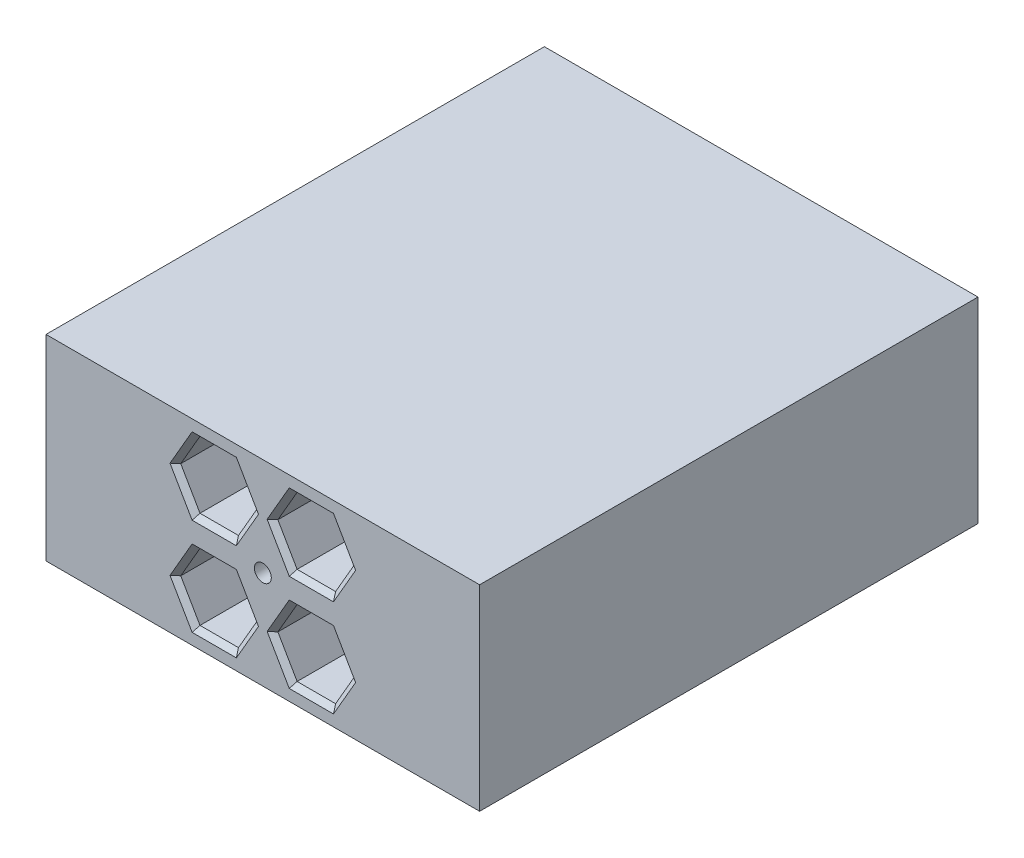
SolidWorks part; units mm, degrees
ref_plane "Front Plane" through (0, 0, 0) normal (0, 0, 1) x (1, 0, 0)
ref_plane "Top Plane" through (0, 0, 0) normal (0, 1, 0) x (1, 0, 0)
ref_plane "Right Plane" through (0, 0, 0) normal (1, 0, 0) x (0, 0, -1)
sketch "Sketch1" plane through (0, 0, 0) normal (0, 0, 1) x (1, 0, 0)
  line L1 (0, 0) -> (44.2, 0)
  line L2 (0, 0) -> (0, 20)
  line L3 (0, 20) -> (44.2, 20)
  line L4 (44.2, 0) -> (44.2, 20)
  dimension "D1" = 20
  dimension "D2" = 44.2
extrude "Boss-Extrude1" add sketch "Sketch1" along normal blind 50.8
sketch "Sketch2" plane through (0, 0, 0) normal (0, 0, -1) x (-1, 0, 0)
  line L0 (0, 0) -> (-44.2, 0) construction
  line L1 (-25.0886, 18.3473) -> (-29.0114, 18.3473)
  line L2 (-29.0114, 18.3473) -> (-30.9728, 14.95)
  line L3 (-30.9728, 14.95) -> (-29.0114, 11.5527)
  line L4 (-29.0114, 11.5527) -> (-25.0886, 11.5527)
  line L5 (-25.0886, 11.5527) -> (-23.1272, 14.95)
  line L6 (-23.1272, 14.95) -> (-25.0886, 18.3473)
  line L7 (-15.1886, 18.3473) -> (-19.1114, 18.3472)
  line L8 (-19.1114, 18.3472) -> (-21.0728, 14.95)
  line L9 (-21.0728, 14.95) -> (-19.1114, 11.5528)
  line L10 (-19.1114, 11.5528) -> (-15.1886, 11.5528)
  line L11 (-15.1886, 11.5528) -> (-13.2272, 14.95)
  line L12 (-13.2272, 14.95) -> (-15.1886, 18.3473)
  line L13 (-15.1886, 8.4473) -> (-19.1114, 8.4473)
  line L14 (-19.1114, 8.4473) -> (-21.0728, 5.05)
  line L15 (-21.0728, 5.05) -> (-19.1114, 1.6528)
  line L16 (-19.1114, 1.6528) -> (-15.1886, 1.6528)
  line L17 (-15.1886, 1.6528) -> (-13.2272, 5.05)
  line L18 (-13.2272, 5.05) -> (-15.1886, 8.4473)
  line L19 (-25.0886, 8.4473) -> (-29.0114, 8.4473)
  line L20 (-29.0114, 8.4473) -> (-30.9728, 5.05)
  line L21 (-30.9728, 5.05) -> (-29.0114, 1.6528)
  line L22 (-29.0114, 1.6528) -> (-25.0886, 1.6528)
  line L23 (-25.0886, 1.6528) -> (-23.1272, 5.05)
  line L24 (-23.1272, 5.05) -> (-25.0886, 8.4473)
  line L25 (0, 20) -> (0, 0) construction
  circle A0 centre (-27.05, 14.95) radius 3.3973 construction
  circle A1 centre (-17.15, 14.95) radius 3.3972 construction
  circle A2 centre (-17.15, 5.05) radius 3.3973 construction
  circle A3 centre (-27.05, 5.05) radius 3.3973 construction
  circle A4 centre (-22.1, 10) radius 0.8634
  point P39 (-17.15, 18.3473)
  dimension "D1" = 0
  dimension "D2" = 0
  dimension "D3" = 0
  dimension "D4" = 0
  dimension "D5" = 10
  dimension "D6" = 22.1
  dimension "D7" = 4.95
  dimension "D8" = 4.95
  dimension "D9" = 9.9
  dimension "D10" = 9.9
  dimension "D11" = 9.9
  dimension "D12" = 9.9
  dimension "D13" = 0
  dimension "D14" = 0
  dimension "D15" = 6.7945
  dimension "D16" = 6.7945
  dimension "D17" = 6.7945
  dimension "D18" = 6.7945
extrude "Cut-Extrude1" cut sketch "Sketch2" against normal blind 6.35
chamfer "Chamfer1" distance 0.508 angle 45 24 edges at (20.0921, 6.7486, 0) (20.0921, 3.3514, 0) (17.15, 1.6528, 0) (14.2079, 3.3514, 0) (14.2079, 6.7486, 0) (17.15, 8.4473, 0) (20.0921, 13.2514, 0) (17.15, 11.5528, 0) (14.2079, 13.2514, 0) (14.2079, 16.6486, 0) (17.15, 18.3473, 0) (20.0921, 16.6486, 0) (24.1079, 6.7486, 0) (24.1079, 3.3514, 0) (27.05, 1.6528, 0) (29.9921, 3.3514, 0) (29.9921, 6.7486, 0) (27.05, 8.4473, 0) (24.1079, 13.2514, 0) (27.05, 11.5527, 0) (24.1079, 16.6486, 0) (27.05, 18.3473, 0) (29.9921, 16.6486, 0) (29.9921, 13.2514, 0)
ref_plane "Plane1" through (0, 0, 25.4) normal (0, 0, -1) x (-1, 0, 0)
mirror "Mirror2" about plane through (0, 0, 25.4) normal (0, 0, -1) of "Chamfer1", "Cut-Extrude1"
equation "\"standoff\"= 0.2675"
equation "\"D15@Sketch2\"=\"standoff\""
equation "\"D16@Sketch2\"=\"standoff\""
equation "\"D17@Sketch2\"=\"standoff\""
equation "\"D18@Sketch2\"=\"standoff\""
